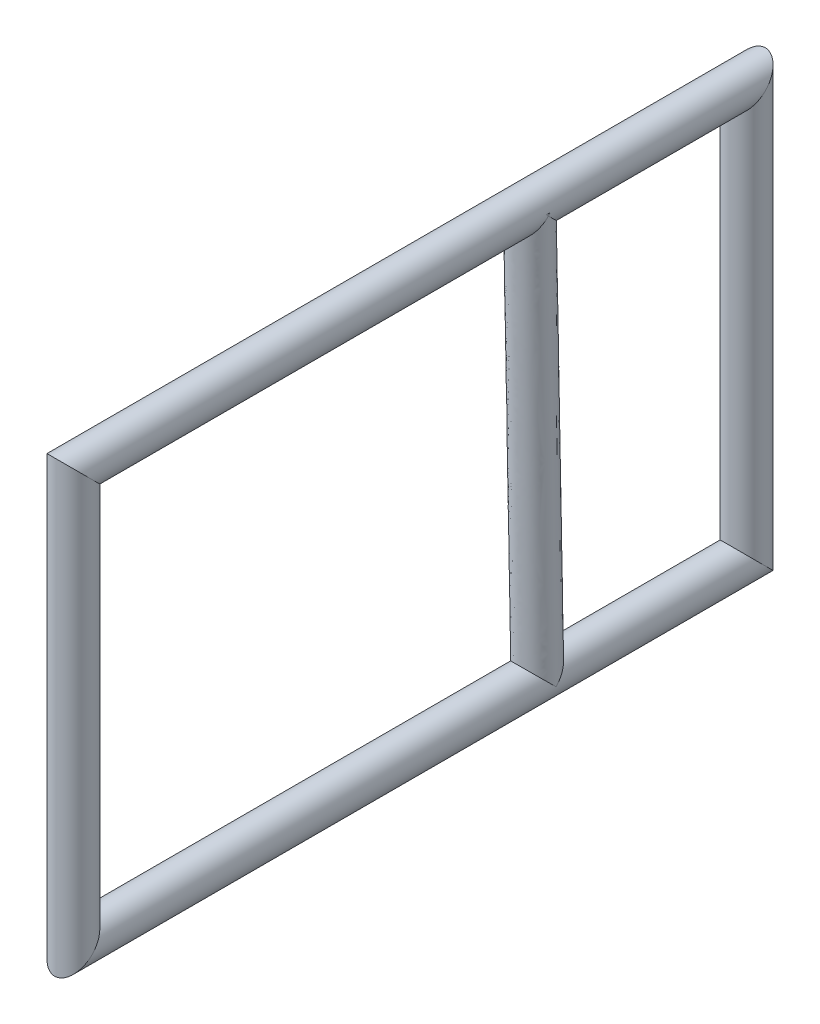
SolidWorks part; units mm, degrees
ref_plane "Front Plane" through (0, 0, 0) normal (0, 0, 1) x (1, 0, 0)
ref_plane "Top Plane" through (0, 0, 0) normal (0, 1, 0) x (1, 0, 0)
ref_plane "Right Plane" through (0, 0, 0) normal (1, 0, 0) x (0, 0, -1)
sketch "Sketch2" plane through (0, 0, 0) normal (0, 0, 1) x (1, 0, 0)
  circle A0 centre (0, 0) radius 12.7
sketch "Sketch3" plane through (0, 0, 0) normal (1, 0, 0) x (0, 0, -1)
  line L0 (0, 0) -> (-457.2, 0)
  line L1 (-457.2, 0) -> (-457.2, 279.4)
  line L2 (-457.2, 279.4) -> (0, 279.4)
  line L3 (0, 279.4) -> (0, 0)
sweep "Sweep1" add profiles "Sketch2" path "Sketch3"
sketch "Sketch4" plane through (0, 0, 0) normal (1, 0, 0) x (0, 0, -1)
  line L0 (-142.064, 0) -> (-147.3314, 280.7913)
sketch "Sketch5" plane through (0, 0, 0) normal (0, 1, 0) x (1, 0, 0)
  circle A0 centre (0, -142.064) radius 12.7
sweep "Sweep2" add profiles "Sketch5" path "Sketch4"
